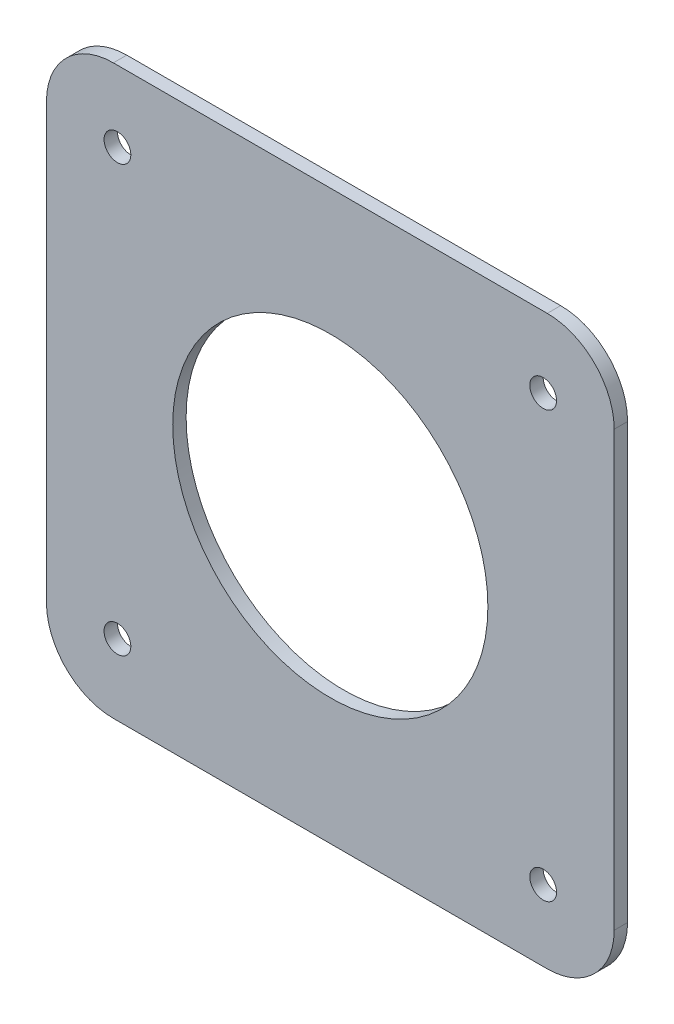
SolidWorks part; units mm, degrees
ref_plane "Front Plane" through (0, 0, 0) normal (0, 0, 1) x (1, 0, 0)
ref_plane "Top Plane" through (0, 0, 0) normal (0, 1, 0) x (1, 0, 0)
ref_plane "Right Plane" through (0, 0, 0) normal (1, 0, 0) x (0, 0, -1)
sketch "Sketch1" plane through (0, 0, 0) normal (0, 0, 1) x (1, 0, 0)
  line L1 (-5.5355, 65.4307) -> (59.3145, 65.4307)
  line L2 (-15.5355, 55.4307) -> (-15.5355, -9.4193)
  line L3 (-5.5355, -19.4193) -> (59.3145, -19.4193)
  line L4 (69.3145, 55.4307) -> (69.3145, -9.4193)
  circle A0 centre (26.8895, 23.0057) radius 23.55
  arc A1 (59.3145, 65.4307) -> (69.3145, 55.4307) centre (59.3145, 55.4307) cw
  arc A2 (59.3145, -19.4193) -> (69.3145, -9.4193) centre (59.3145, -9.4193) ccw
  arc A3 (-15.5355, -9.4193) -> (-5.5355, -19.4193) centre (-5.5355, -9.4193) ccw
  arc A4 (-5.5355, 65.4307) -> (-15.5355, 55.4307) centre (-5.5355, 55.4307) ccw
  circle A5 centre (-4.9255, 54.8207) radius 2
  circle A6 centre (-4.9255, -8.8093) radius 2
  circle A7 centre (58.7045, 54.8207) radius 2
  circle A8 centre (58.7045, -8.8093) radius 2
  dimension "D1" = 10
  dimension "D2" = 10
  dimension "D3" = 10
  dimension "D4" = 10
  dimension "D5" = 47.1
extrude "Boss-Extrude1" add sketch "Sketch1" along normal blind 2
